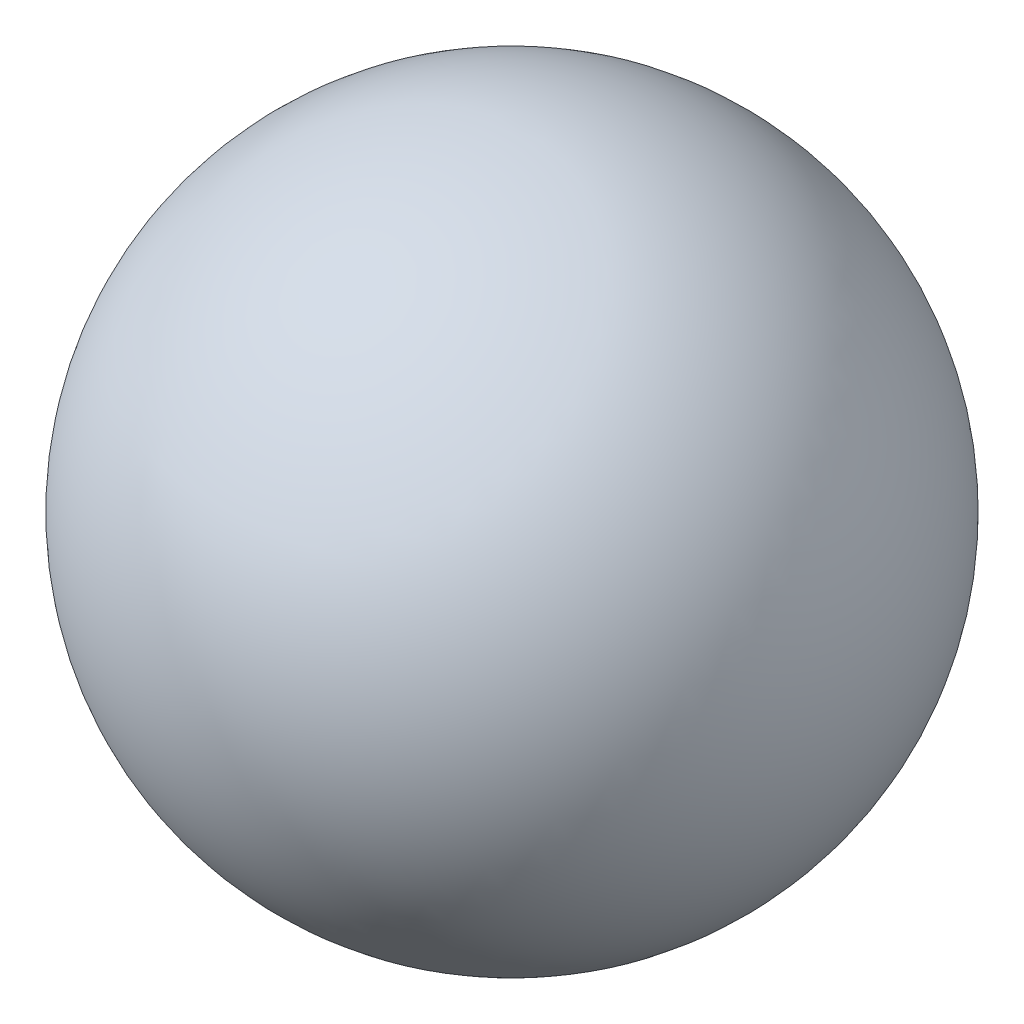
SolidWorks part; units mm, degrees
ref_plane "Front Plane" through (0, 0, 0) normal (0, 0, 1) x (1, 0, 0)
ref_plane "Top Plane" through (0, 0, 0) normal (0, 1, 0) x (1, 0, 0)
ref_plane "Right Plane" through (0, 0, 0) normal (1, 0, 0) x (0, 0, -1)
sketch "Sketch1" plane through (0, 0, 0) normal (0, 0, 1) x (1, 0, 0)
  line L0 (0, -95) -> (0, 95) construction
  line L1 (0, 95) -> (0, -95)
  arc A0 (0, 95) -> (0, -95) centre (0, 0) ccw
  dimension "D2" = 95
  dimension "D1" = 190
revolve "Revolve1" add sketch "Sketch1" angle 360 about L0
